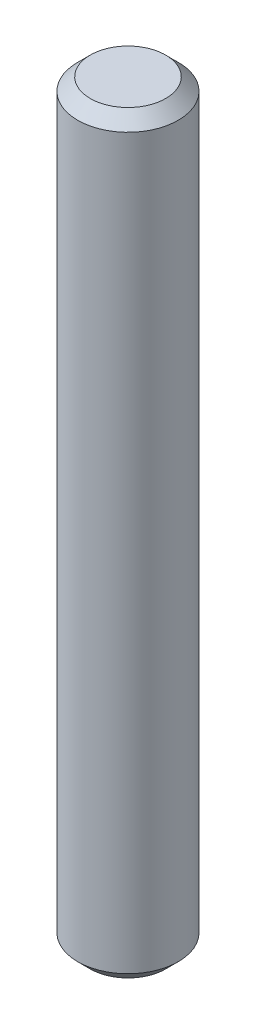
SolidWorks part; units mm, degrees
ref_plane "Front Plane" through (0, 0, 0) normal (0, 0, 1) x (1, 0, 0)
ref_plane "Top Plane" through (0, 0, 0) normal (0, 1, 0) x (1, 0, 0)
ref_plane "Right Plane" through (0, 0, 0) normal (1, 0, 0) x (0, 0, -1)
sketch "Sketch2" plane through (0, 0, 0) normal (0, 1, 0) x (1, 0, 0)
  circle A0 centre (0, 0) radius 2
  dimension "D1" = 4
extrude "Boss-Extrude1" add sketch "Sketch2" along normal mid plane 30
chamfer "Chamfer1" distance 0.5 angle 45 2 edges at (0, -15, 2) (0, 15, 2)
